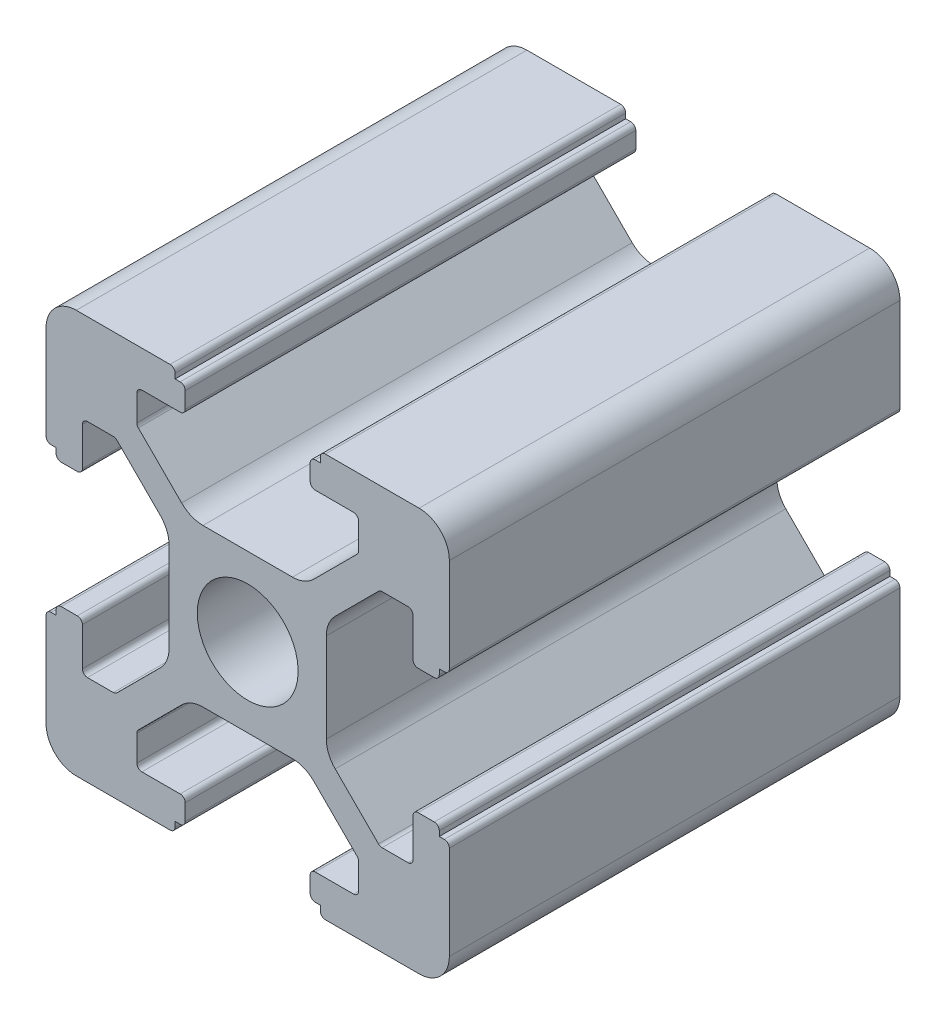
SolidWorks part; units mm, degrees
ref_plane "前视基准面" through (0, 0, 0) normal (0, 0, 1) x (1, 0, 0)
ref_plane "上视基准面" through (0, 0, 0) normal (0, 1, 0) x (1, 0, 0)
ref_plane "右视基准面" through (0, 0, 0) normal (1, 0, 0) x (0, 0, -1)
sketch "草图1" plane through (0, 0, 0) normal (0, 0, 1) x (1, 0, 0)
  line L0 (0, 0) -> (0, 5.5) construction
  line L1 (-8.5023, -10.0023) -> (-3.85, -10.0023)
  line L2 (-10.0023, -8.5023) -> (-10.0023, -3.85)
  line L3 (-8.5023, 10.0023) -> (-3.85, 10.0023)
  line L4 (10.0023, -8.5023) -> (10.0023, -3.85)
  line L5 (-10.0023, -10.0023) -> (10.0023, 10.0023) construction
  line L6 (-10.0023, 10.0023) -> (10.0023, -10.0023) construction
  line L7 (-2.218, -3.9) -> (2.218, -3.9)
  line L8 (-3.9, -2.218) -> (-3.9, 2.218)
  line L9 (-2.218, 3.9) -> (2.218, 3.9)
  line L10 (3.9, -2.218) -> (3.9, 2.218)
  line L11 (-3.9, -3.9) -> (3.9, 3.9) construction
  line L12 (-3.9, 3.9) -> (3.9, -3.9) construction
  line L13 (-5.25, -8.2) -> (-3.35, -8.2)
  line L14 (-8.2, -5.25) -> (-8.2, -3.35)
  line L15 (-5.25, 8.2) -> (-3.35, 8.2)
  line L16 (8.2, -5.25) -> (8.2, -3.35)
  line L17 (-8.2, -8.2) -> (8.2, 8.2) construction
  line L18 (-8.2, 8.2) -> (8.2, -8.2) construction
  line L19 (-7.95, 5.5) -> (-6.6642, 5.5)
  line L20 (0, 0) -> (5.5, 0) construction
  line L23 (-5.5, 7.95) -> (-5.5, 6.6642)
  line L26 (0, 0) -> (-0.5303, 0.5303)
  line L27 (3.2787, 4.3393) -> (5.4268, 6.4874)
  line L28 (0, 0) -> (0.5303, -0.5303)
  line L29 (5.5, 6.6642) -> (5.5, 7.95)
  line L30 (4.3393, 3.2787) -> (6.4874, 5.4268)
  line L31 (6.6642, 5.5) -> (7.95, 5.5)
  line L32 (4.3393, -3.2787) -> (6.4874, -5.4268)
  line L33 (3.2787, -4.3393) -> (5.4268, -6.4874)
  line L34 (-3.2787, -4.3393) -> (-5.4268, -6.4874)
  line L35 (-4.3393, -3.2787) -> (-6.4874, -5.4268)
  line L36 (-4.3393, 3.2787) -> (-6.4874, 5.4268)
  line L37 (-3.2787, 4.3393) -> (-5.4268, 6.4874)
  line L38 (3.1, -8.45) -> (3.1, -9.2523)
  line L39 (8.45, 3.1) -> (9.2523, 3.1)
  line L40 (-5.5, -6.6642) -> (-5.5, -7.95)
  line L41 (-6.6642, -5.5) -> (-7.95, -5.5)
  line L42 (5.5, -6.6642) -> (5.5, -7.95)
  line L43 (6.6642, -5.5) -> (7.95, -5.5)
  line L44 (9.2523, -3.1) -> (8.45, -3.1)
  line L46 (10.0023, 3.85) -> (10.0023, 8.5023)
  line L47 (8.2, 3.35) -> (8.2, 5.25)
  line L48 (-3.1, -9.2523) -> (-3.1, -8.45)
  line L49 (-8.45, -3.1) -> (-9.2523, -3.1)
  line L50 (-9.2523, 3.1) -> (-8.45, 3.1)
  line L51 (-3.1, 8.45) -> (-3.1, 9.2523)
  line L52 (3.1, 9.2523) -> (3.1, 8.45)
  line L53 (3.85, 10.0023) -> (8.5023, 10.0023)
  line L54 (3.35, 8.2) -> (5.25, 8.2)
  line L55 (-10.0023, 3.85) -> (-10.0023, 8.5023)
  line L56 (-8.2, 3.35) -> (-8.2, 5.25)
  line L57 (3.35, -8.2) -> (5.25, -8.2)
  line L58 (3.85, -10.0023) -> (8.5023, -10.0023)
  line L59 (9.7523, -3.6) -> (9.5023, -3.6)
  line L61 (9.7523, 3.6) -> (9.5023, 3.6)
  line L62 (9.5023, -3.6) -> (9.5023, -3.35)
  line L63 (3.6, -9.7523) -> (3.6, -9.5023)
  line L64 (3.35, -9.5023) -> (3.6, -9.5023)
  line L65 (9.5023, 3.35) -> (9.5023, 3.6)
  line L66 (-3.6, -9.5023) -> (-3.35, -9.5023)
  line L67 (-3.6, -9.7523) -> (-3.6, -9.5023)
  line L68 (-9.7523, -3.6) -> (-9.5023, -3.6)
  line L69 (-9.5023, -3.35) -> (-9.5023, -3.6)
  line L70 (-9.5023, 3.6) -> (-9.5023, 3.35)
  line L71 (-9.7523, 3.6) -> (-9.5023, 3.6)
  line L72 (-3.6, 9.7523) -> (-3.6, 9.5023)
  line L73 (-3.35, 9.5023) -> (-3.6, 9.5023)
  line L74 (3.6, 9.5023) -> (3.35, 9.5023)
  line L75 (3.6, 9.7523) -> (3.6, 9.5023)
  circle A0 centre (0, 0) radius 2.5
  arc A1 (10.0023, 8.5023) -> (8.5023, 10.0023) centre (8.5023, 8.5023) ccw
  arc A2 (8.5023, -10.0023) -> (10.0023, -8.5023) centre (8.5023, -8.5023) ccw
  arc A3 (-10.0023, -8.5023) -> (-8.5023, -10.0023) centre (-8.5023, -8.5023) ccw
  arc A4 (-10.0023, 8.5023) -> (-8.5023, 10.0023) centre (-8.5023, 8.5023) cw
  arc A5 (-9.5023, -3.35) -> (-9.2523, -3.1) centre (-9.2523, -3.35) cw
  arc A6 (-9.7523, -3.6) -> (-10.0023, -3.85) centre (-9.7523, -3.85) ccw
  arc A7 (-8.45, -3.1) -> (-8.2, -3.35) centre (-8.45, -3.35) cw
  arc A8 (-7.95, -5.5) -> (-8.2, -5.25) centre (-7.95, -5.25) cw
  arc A9 (-6.4874, -5.4268) -> (-6.6642, -5.5) centre (-6.6642, -5.25) cw
  arc A10 (-5.4268, -6.4874) -> (-5.5, -6.6642) centre (-5.25, -6.6642) ccw
  arc A11 (-5.5, -7.95) -> (-5.25, -8.2) centre (-5.25, -7.95) ccw
  arc A12 (-3.6, -9.7523) -> (-3.85, -10.0023) centre (-3.85, -9.7523) cw
  arc A13 (-3.35, -9.5023) -> (-3.1, -9.2523) centre (-3.35, -9.2523) ccw
  arc A14 (-3.1, -8.45) -> (-3.35, -8.2) centre (-3.35, -8.45) ccw
  arc A15 (3.1, -8.45) -> (3.35, -8.2) centre (3.35, -8.45) cw
  arc A16 (5.5, -7.95) -> (5.25, -8.2) centre (5.25, -7.95) cw
  arc A17 (5.4268, -6.4874) -> (5.5, -6.6642) centre (5.25, -6.6642) cw
  arc A18 (6.4874, -5.4268) -> (6.6642, -5.5) centre (6.6642, -5.25) ccw
  arc A19 (7.95, -5.5) -> (8.2, -5.25) centre (7.95, -5.25) ccw
  arc A20 (8.45, -3.1) -> (8.2, -3.35) centre (8.45, -3.35) ccw
  arc A21 (9.5023, -3.35) -> (9.2523, -3.1) centre (9.2523, -3.35) ccw
  arc A22 (9.7523, -3.6) -> (10.0023, -3.85) centre (9.7523, -3.85) cw
  arc A23 (3.35, -9.5023) -> (3.1, -9.2523) centre (3.35, -9.2523) cw
  arc A24 (3.6, -9.7523) -> (3.85, -10.0023) centre (3.85, -9.7523) ccw
  arc A25 (7.95, 5.5) -> (8.2, 5.25) centre (7.95, 5.25) cw
  arc A26 (8.2, 3.35) -> (8.45, 3.1) centre (8.45, 3.35) ccw
  arc A27 (9.5023, 3.35) -> (9.2523, 3.1) centre (9.2523, 3.35) cw
  arc A28 (9.7523, 3.6) -> (10.0023, 3.85) centre (9.7523, 3.85) ccw
  arc A29 (6.6642, 5.5) -> (6.4874, 5.4268) centre (6.6642, 5.25) ccw
  arc A30 (5.4268, 6.4874) -> (5.5, 6.6642) centre (5.25, 6.6642) ccw
  arc A31 (5.5, 7.95) -> (5.25, 8.2) centre (5.25, 7.95) ccw
  arc A32 (3.1, 8.45) -> (3.35, 8.2) centre (3.35, 8.45) ccw
  arc A33 (3.6, 9.7523) -> (3.85, 10.0023) centre (3.85, 9.7523) cw
  arc A34 (3.35, 9.5023) -> (3.1, 9.2523) centre (3.35, 9.2523) ccw
  arc A35 (-9.7523, 3.6) -> (-10.0023, 3.85) centre (-9.7523, 3.85) cw
  arc A36 (-9.5023, 3.35) -> (-9.2523, 3.1) centre (-9.2523, 3.35) ccw
  arc A37 (-8.45, 3.1) -> (-8.2, 3.35) centre (-8.45, 3.35) ccw
  arc A38 (-8.2, 5.25) -> (-7.95, 5.5) centre (-7.95, 5.25) cw
  arc A39 (-6.4874, 5.4268) -> (-6.6642, 5.5) centre (-6.6642, 5.25) ccw
  arc A40 (-5.4268, 6.4874) -> (-5.5, 6.6642) centre (-5.25, 6.6642) cw
  arc A41 (-5.5, 7.95) -> (-5.25, 8.2) centre (-5.25, 7.95) cw
  arc A42 (-3.1, 8.45) -> (-3.35, 8.2) centre (-3.35, 8.45) cw
  arc A43 (-3.1, 9.2523) -> (-3.35, 9.5023) centre (-3.35, 9.2523) ccw
  arc A44 (-3.6, 9.7523) -> (-3.85, 10.0023) centre (-3.85, 9.7523) ccw
  arc A45 (-4.3393, 3.2787) -> (-3.9, 2.218) centre (-5.4, 2.218) cw
  arc A46 (-3.2787, 4.3393) -> (-2.218, 3.9) centre (-2.218, 5.4) ccw
  arc A47 (3.2787, 4.3393) -> (2.218, 3.9) centre (2.218, 5.4) cw
  arc A48 (4.3393, 3.2787) -> (3.9, 2.218) centre (5.4, 2.218) ccw
  arc A49 (4.3393, -3.2787) -> (3.9, -2.218) centre (5.4, -2.218) cw
  arc A50 (3.2787, -4.3393) -> (2.218, -3.9) centre (2.218, -5.4) ccw
  arc A51 (-4.3393, -3.2787) -> (-3.9, -2.218) centre (-5.4, -2.218) ccw
  arc A52 (-2.218, -3.9) -> (-3.2787, -4.3393) centre (-2.218, -5.4) ccw
  point P0 (0, 0)
  point P7 (10.0023, 0)
  point P62 (0, 0)
  point P76 (0, 0)
  point P92 (-8.2, -5.5)
  point P99 (0, 0)
  point P106 (-5.5, -8.2)
  point P117 (5.5, -8.2)
  point P124 (8.2, -5.5)
  point P137 (8.2, 5.5)
  point P140 (8.2, 3.1)
  point P147 (6.5607, 5.5)
  point P152 (5.5, 8.2)
  point P167 (-8.2, 5.5)
  point P174 (-5.5, 8.2)
  dimension "D1" = 1.5
  dimension "D5" = 0.25
  dimension "D6" = 1.5
  dimension "D2" = 4
  dimension "D3" = 4
  dimension "D4" = 4
extrude "凸台-拉伸1" add sketch "草图1" along normal blind 22.35 contours A52 L7 A50 L33 A17 L42 A16 L57 A15 L38 A23 L64 L63 A24 L58 A2 L4 A22 L59 L62 A21 L44 A20 L16 A19 L43 A18 L32 A49 L10 A48 L30 A29 L31 A25 L47 A26 L39 A27 L65 L61 A28 L46 A1 L53 A33 L75 L74 A34 L52 A32
